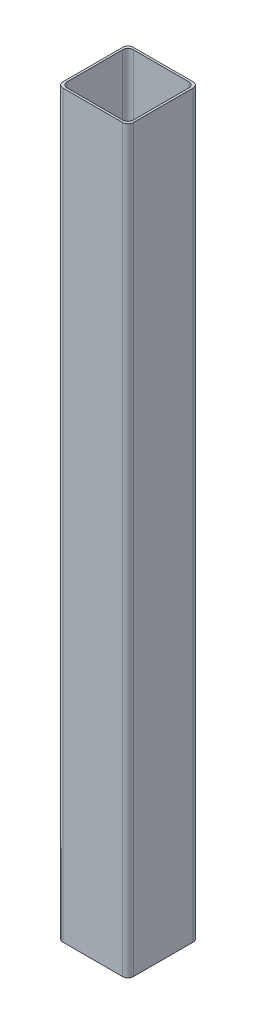
SolidWorks part; units mm, degrees
ref_plane "Plano frontal" through (0, 0, 0) normal (0, 0, 1) x (1, 0, 0)
ref_plane "Plano superior" through (0, 0, 0) normal (0, 1, 0) x (1, 0, 0)
ref_plane "Plano direito" through (0, 0, 0) normal (1, 0, 0) x (0, 0, -1)
sketch "Esboço1" plane through (0, 0, 0) normal (0, 1, 0) x (1, 0, 0)
  line L0 (-18.8, -18.8) -> (-18.8, 18.8)
  line L1 (20, -20) -> (-20, -20)
  line L2 (20, -20) -> (20, 20)
  line L3 (20, 20) -> (-20, 20)
  line L4 (-20, -20) -> (-20, 20)
  line L5 (20, -20) -> (-20, 20) construction
  line L6 (20, 20) -> (-20, -20) construction
  line L7 (18.8, 18.8) -> (-18.8, 18.8)
  line L8 (18.8, -18.8) -> (18.8, 18.8)
  line L9 (18.8, -18.8) -> (-18.8, -18.8)
  point P0 (0, 0)
  dimension "D1" = 40
  dimension "D2" = 40
  dimension "D3" = 1.2
extrude "Ressalto-extrusão1" add sketch "Esboço1" along normal mid plane 420
fillet "Filete1" radius 3 8 edges at (-20, 0, -20) (20, 0, -20) (18.8, 0, -18.8) (18.8, 0, 18.8) (-18.8, 0, 18.8) (-18.8, 0, -18.8) (-20, 0, 20) (20, 0, 20)
